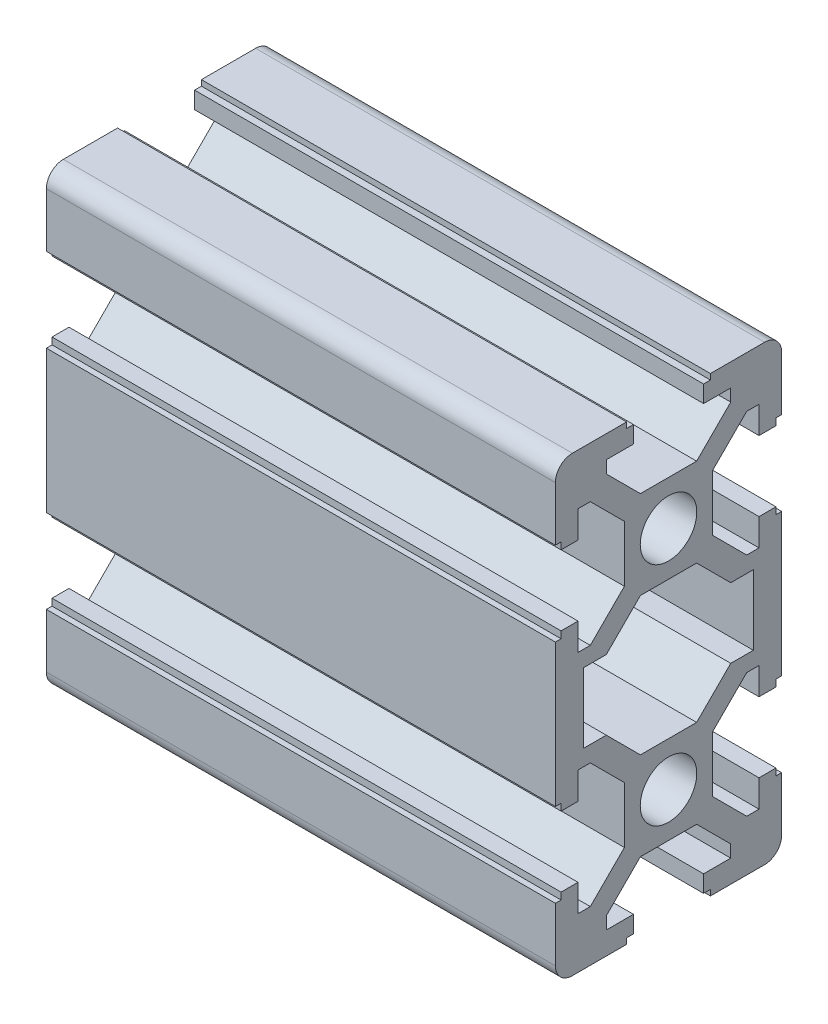
SolidWorks part; units mm, degrees
ref_plane "前视基准面" through (0, 0, 0) normal (0, 0, 1) x (1, 0, 0)
ref_plane "上视基准面" through (0, 0, 0) normal (0, 1, 0) x (1, 0, 0)
ref_plane "右视基准面" through (0, 0, 0) normal (1, 0, 0) x (0, 0, -1)
other "Configuration Table"
ref_plane "基准面1" through (0, 0, 9.923) normal (0, 0, 1) x (1, 0, 0)
sketch "草图1" plane through (0, 0, 9.923) normal (0, 0, 1) x (1, 0, 0)
  line L0 (-1048, 19.9963) -> (-1048, -20.0037)
  line L1 (-1048, -20.0037) -> (0, -20.0037)
  line L2 (0, -20.0037) -> (0, 19.9963)
  line L3 (0, 19.9963) -> (-1048, 19.9963)
extrude "凸台-拉伸1" add sketch "草图1" against normal blind 20
sketch "草图2" plane through (0, 0, 0) normal (1, 0, 0) x (0, 0, -1)
  line L0 (-3.023, 19.9963) -> (-3.023, 17.9963)
  line L1 (-3.023, 17.9963) -> (-5.423, 17.9963)
  line L2 (-5.423, 17.9963) -> (-5.423, 16.9105)
  line L3 (-5.423, 16.9105) -> (-2.4088, 13.8963)
  line L4 (-2.4088, 13.8963) -> (2.5628, 13.8963)
  line L5 (2.5628, 13.8963) -> (5.577, 16.9105)
  line L6 (5.577, 16.9105) -> (5.577, 17.9963)
  line L7 (5.577, 17.9963) -> (3.177, 17.9963)
  line L8 (3.177, 17.9963) -> (3.177, 19.9963)
  line L9 (3.177, 19.9963) -> (-3.023, 19.9963)
extrude "切除-拉伸1" cut sketch "草图2" against normal through all
sketch "草图3" plane through (0, 19.9963, 0) normal (0, 1, 0) x (-1, 0, 0)
  line L0 (9.0173, 3.023) -> (16.9827, 3.023)
  arc A0 (16.9827, 3.023) -> (9.0173, 3.023) centre (13, 0) ccw
extrude "切除-拉伸2" cut sketch "草图3" against normal up to next
sketch "草图4" plane through (-1048, 0, 0) normal (-1, 0, 0) x (0, 0, 1)
  line L0 (3.023, 19.4963) -> (3.628, 19.4963)
  line L1 (3.628, 19.4963) -> (3.628, 19.9963)
  line L2 (3.628, 19.9963) -> (3.023, 19.9963)
  line L3 (3.023, 19.9963) -> (3.023, 19.4963)
extrude "切除-拉伸3" cut sketch "草图4" against normal up to next
sketch "草图5" plane through (0, 0, 0) normal (1, 0, 0) x (0, 0, -1)
  line L0 (-3.023, -20.0037) -> (3.177, -20.0037)
  line L1 (3.177, -20.0037) -> (3.177, -18.0037)
  line L2 (3.177, -18.0037) -> (5.577, -18.0037)
  line L3 (5.577, -18.0037) -> (5.577, -16.9179)
  line L4 (5.577, -16.9179) -> (2.5628, -13.9037)
  line L5 (2.5628, -13.9037) -> (-2.4088, -13.9037)
  line L6 (-2.4088, -13.9037) -> (-5.423, -16.9179)
  line L7 (-5.423, -16.9179) -> (-5.423, -18.0037)
  line L8 (-5.423, -18.0037) -> (-3.023, -18.0037)
  line L9 (-3.023, -18.0037) -> (-3.023, -20.0037)
extrude "切除-拉伸4" cut sketch "草图5" against normal through all
sketch "草图6" plane through (0, -18.0037, 0) normal (0, 1, 0) x (-1, 0, 0)
  line L0 (9.0173, 3.023) -> (16.9827, 3.023)
  arc A0 (16.9827, 3.023) -> (9.0173, 3.023) centre (13, 0) ccw
extrude "切除-拉伸5" cut sketch "草图6" against normal through all
sketch "草图7" plane through (-1048, 0, 0) normal (-1, 0, 0) x (0, 0, 1)
  line L0 (3.023, -20.0037) -> (3.628, -20.0037)
  line L1 (3.628, -20.0037) -> (3.628, -19.5037)
  line L2 (3.628, -19.5037) -> (3.023, -19.5037)
  line L3 (3.023, -19.5037) -> (3.023, -20.0037)
extrude "切除-拉伸6" cut sketch "草图7" against normal up to next
sketch "草图8" plane through (0, -20.0037, 0) normal (0, -1, 0) x (1, 0, 0)
  line L0 (-9.1391, -3.177) -> (-16.8609, -3.177)
  arc A0 (-16.8609, -3.177) -> (-9.1391, -3.177) centre (-13, 0) ccw
extrude "切除-拉伸7" cut sketch "草图8" against normal up to next
sketch "草图9" plane through (-1048, 0, 0) normal (-1, 0, 0) x (0, 0, 1)
  line L0 (-3.177, -20.0037) -> (-3.177, -19.5037)
  line L1 (-3.177, -19.5037) -> (-3.782, -19.5037)
  line L2 (-3.782, -19.5037) -> (-3.782, -20.0037)
  line L3 (-3.782, -20.0037) -> (-3.177, -20.0037)
extrude "切除-拉伸8" cut sketch "草图9" against normal up to next
sketch "草图10" plane through (0, 0, 0) normal (1, 0, 0) x (0, 0, -1)
  line L0 (-3.628, 19.9963) -> (-3.628, 19.4963)
  line L1 (-3.628, 19.4963) -> (-3.023, 19.4963)
  line L2 (-3.023, 19.4963) -> (-3.023, 19.9963)
  line L3 (-3.023, 19.9963) -> (-3.628, 19.9963)
extrude "切除-拉伸9" cut sketch "草图10" against normal up to next
sketch "草图11" plane through (0, 17.9963, 0) normal (0, -1, 0) x (1, 0, 0)
  line L0 (-9.1391, -3.177) -> (-16.8609, -3.177)
  arc A0 (-16.8609, -3.177) -> (-9.1391, -3.177) centre (-13, 0) ccw
extrude "切除-拉伸10" cut sketch "草图11" against normal through all
sketch "草图12" plane through (0, 0, 0) normal (1, 0, 0) x (0, 0, -1)
  line L0 (3.177, 19.9963) -> (3.177, 19.4963)
  line L1 (3.177, 19.4963) -> (3.782, 19.4963)
  line L2 (3.782, 19.4963) -> (3.782, 19.9963)
  line L3 (3.782, 19.9963) -> (3.177, 19.9963)
extrude "切除-拉伸11" cut sketch "草图12" against normal up to next
sketch "草图13" plane through (0, 0, 0) normal (1, 0, 0) x (0, 0, -1)
  line L0 (10.077, 13.7013) -> (9.577, 13.7013)
  line L1 (9.577, 13.7013) -> (9.577, 13.0963)
  line L2 (9.577, 13.0963) -> (8.077, 13.0963)
  line L3 (8.077, 13.0963) -> (8.077, 15.4963)
  line L4 (8.077, 15.4963) -> (6.9912, 15.4963)
  line L5 (6.9912, 15.4963) -> (3.977, 12.4821)
  line L6 (3.977, 12.4821) -> (3.977, 7.5105)
  line L7 (3.977, 7.5105) -> (6.9912, 4.4963)
  line L8 (6.9912, 4.4963) -> (8.077, 4.4963)
  line L9 (8.077, 4.4963) -> (8.077, 6.8963)
  line L10 (8.077, 6.8963) -> (9.577, 6.8963)
  line L11 (9.577, 6.8963) -> (9.577, 6.2913)
  line L12 (9.577, 6.2913) -> (10.077, 6.2913)
  line L13 (10.077, 6.2913) -> (10.077, 13.7013)
extrude "切除-拉伸12" cut sketch "草图13" against normal through all
sketch "草图14" plane through (0, 0, 0) normal (1, 0, 0) x (0, 0, -1)
  line L0 (10.077, -6.2987) -> (9.577, -6.2987)
  line L1 (9.577, -6.2987) -> (9.577, -6.9037)
  line L2 (9.577, -6.9037) -> (8.077, -6.9037)
  line L3 (8.077, -6.9037) -> (8.077, -4.5037)
  line L4 (8.077, -4.5037) -> (6.9912, -4.5037)
  line L5 (6.9912, -4.5037) -> (3.977, -7.5179)
  line L6 (3.977, -7.5179) -> (3.977, -12.4895)
  line L7 (3.977, -12.4895) -> (6.9912, -15.5037)
  line L8 (6.9912, -15.5037) -> (8.077, -15.5037)
  line L9 (8.077, -15.5037) -> (8.077, -13.1037)
  line L10 (8.077, -13.1037) -> (9.577, -13.1037)
  line L11 (9.577, -13.1037) -> (9.577, -13.7087)
  line L12 (9.577, -13.7087) -> (10.077, -13.7087)
  line L13 (10.077, -13.7087) -> (10.077, -6.2987)
extrude "切除-拉伸13" cut sketch "草图14" against normal through all
sketch "草图15" plane through (0, 0, 0) normal (1, 0, 0) x (0, 0, -1)
  line L0 (3.782, -20.0037) -> (3.782, -19.5037)
  line L1 (3.782, -19.5037) -> (3.177, -19.5037)
  line L2 (3.177, -19.5037) -> (3.177, -20.0037)
  line L3 (3.177, -20.0037) -> (3.782, -20.0037)
extrude "切除-拉伸14" cut sketch "草图15" against normal up to next
sketch "草图16" plane through (0, 0, 0) normal (1, 0, 0) x (0, 0, -1)
  line L0 (-3.023, -20.0037) -> (-3.023, -19.5037)
  line L1 (-3.023, -19.5037) -> (-3.628, -19.5037)
  line L2 (-3.628, -19.5037) -> (-3.628, -20.0037)
  line L3 (-3.628, -20.0037) -> (-3.023, -20.0037)
extrude "切除-拉伸15" cut sketch "草图16" against normal up to next
sketch "草图17" plane through (0, 0, 0) normal (1, 0, 0) x (0, 0, -1)
  line L0 (-9.923, -13.7087) -> (-9.423, -13.7087)
  line L1 (-9.423, -13.7087) -> (-9.423, -13.1037)
  line L2 (-9.423, -13.1037) -> (-7.923, -13.1037)
  line L3 (-7.923, -13.1037) -> (-7.923, -15.5037)
  line L4 (-7.923, -15.5037) -> (-6.8372, -15.5037)
  line L5 (-6.8372, -15.5037) -> (-3.823, -12.4895)
  line L6 (-3.823, -12.4895) -> (-3.823, -7.5179)
  line L7 (-3.823, -7.5179) -> (-6.8372, -4.5037)
  line L8 (-6.8372, -4.5037) -> (-7.923, -4.5037)
  line L9 (-7.923, -4.5037) -> (-7.923, -6.9037)
  line L10 (-7.923, -6.9037) -> (-9.423, -6.9037)
  line L11 (-9.423, -6.9037) -> (-9.423, -6.2987)
  line L12 (-9.423, -6.2987) -> (-9.923, -6.2987)
  line L13 (-9.923, -6.2987) -> (-9.923, -13.7087)
extrude "切除-拉伸16" cut sketch "草图17" against normal through all
sketch "草图18" plane through (0, 0, 0) normal (1, 0, 0) x (0, 0, -1)
  line L0 (-9.923, 6.2913) -> (-9.423, 6.2913)
  line L1 (-9.423, 6.2913) -> (-9.423, 6.8963)
  line L2 (-9.423, 6.8963) -> (-7.923, 6.8963)
  line L3 (-7.923, 6.8963) -> (-7.923, 4.4963)
  line L4 (-7.923, 4.4963) -> (-6.8372, 4.4963)
  line L5 (-6.8372, 4.4963) -> (-3.823, 7.5105)
  line L6 (-3.823, 7.5105) -> (-3.823, 12.4821)
  line L7 (-3.823, 12.4821) -> (-6.8372, 15.4963)
  line L8 (-6.8372, 15.4963) -> (-7.923, 15.4963)
  line L9 (-7.923, 15.4963) -> (-7.923, 13.0963)
  line L10 (-7.923, 13.0963) -> (-9.423, 13.0963)
  line L11 (-9.423, 13.0963) -> (-9.423, 13.7013)
  line L12 (-9.423, 13.7013) -> (-9.923, 13.7013)
  line L13 (-9.923, 13.7013) -> (-9.923, 6.2913)
extrude "切除-拉伸17" cut sketch "草图18" against normal through all
sketch "草图19" plane through (-1048, 0, 0) normal (-1, 0, 0) x (0, 0, 1)
  line L0 (-3.782, 19.9963) -> (-3.782, 19.4963)
  line L1 (-3.782, 19.4963) -> (-3.177, 19.4963)
  line L2 (-3.177, 19.4963) -> (-3.177, 19.9963)
  line L3 (-3.177, 19.9963) -> (-3.782, 19.9963)
extrude "切除-拉伸18" cut sketch "草图19" against normal up to next
sketch "草图20" plane through (-1048, 0, 0) normal (-1, 0, 0) x (0, 0, 1)
  line L0 (2.4088, -3.0895) -> (7.423, -3.0895)
  line L1 (7.423, -3.0895) -> (7.423, 3.0821)
  line L2 (7.423, 3.0821) -> (2.4088, 3.0821)
  line L3 (2.4088, 3.0821) -> (2.4088, 6.0963)
  line L4 (2.4088, 6.0963) -> (-2.5628, 6.0963)
  line L5 (-2.5628, 6.0963) -> (-2.5628, 3.0821)
  line L6 (-2.5628, 3.0821) -> (-7.577, 3.0821)
  line L7 (-7.577, 3.0821) -> (-7.577, -3.0895)
  line L8 (-7.577, -3.0895) -> (-2.5628, -3.0895)
  line L9 (-2.5628, -3.0895) -> (-2.5628, -6.1037)
  line L10 (-2.5628, -6.1037) -> (2.4088, -6.1037)
  line L11 (2.4088, -6.1037) -> (2.4088, -3.0895)
extrude "切除-拉伸19" cut sketch "草图20" against normal through all
draft "拔模1" type of draft neutral plane draft angle 45 faces to draft 2 face at (-524, -4.5966, 2.4088) face at (-524, -4.5966, -2.5628) neutral plane through (0, -6.1037, -2.5628) neutral plane normal (0, 1, 0) parameters "D1"=45
draft "拔模2" type of draft neutral plane draft angle 45 faces to draft 2 face at (-524, 4.5892, -2.5628) face at (-524, 4.5892, 2.4088) neutral plane through (0, 6.0963, 2.4088) neutral plane normal (0, -1, 0) parameters "D1"=45
ref_plane "基准面2" through (0, 0, 0) normal (0, 0, -1) x (-1, 0, 0)
sketch "草图21" plane through (0, 0, 0) normal (0, 0, -1) x (-1, 0, 0)
  line L0 (8, 10.9963) -> (13, 10.9963)
  line L1 (13, 10.9963) -> (13, 16.4875)
  line L2 (13, 16.4875) -> (8, 16.4875)
  line L3 (8, 16.4875) -> (8, 10.9963)
  line L4 (13, 10.9963) -> (13, 16.4875) construction
revolve "切除-旋转1" cut sketch "草图21" angle 360 about L4
sketch "草图22" plane through (0, 0, 0) normal (0, 0, 1) x (1, 0, 0)
  line L0 (-8, -10.9963) -> (-13, -10.9963)
  line L1 (-13, -10.9963) -> (-13, -16.4949)
  line L2 (-13, -16.4949) -> (-8, -16.4949)
  line L3 (-8, -16.4949) -> (-8, -10.9963)
  line L4 (-13, -10.9963) -> (-13, -16.4949) construction
revolve "切除-旋转2" cut sketch "草图22" angle 360 about L4
hole_wizard "Ø5.0 (5) 直径孔1" positions "草图24" profile "草图23" hole size "Ø5.0" standard "ANSI Metric"
sketch "草图24" plane through (0, 0, 0) normal (1, 0, 0) x (0, 0, -1)
  point P0 (0.077, 9.9963)
sketch "草图23" plane through (0, 9.9963, -0.077) normal (0, 1, 0) x (0, 0, -1)
  line L0 (0, 0) -> (0, 1048)
  line L1 (0, 1048) -> (2.5, 1048)
  line L2 (2.5, 1048) -> (2.5, 0)
  line L5 (2.5, 0) -> (0, 0)
  line L11 (0, -6.35) -> (0, 107.95) construction
  dimension "通孔孔直径" = 5
  dimension "通孔孔深度" = 1048
hole_wizard "Ø5.0 (5) 直径孔2" positions "草图26" profile "草图25" hole size "Ø5.0" standard "ANSI Metric"
sketch "草图26" plane through (-1048, 0, 0) normal (-1, 0, 0) x (0, 0, 1)
  point P0 (-0.077, -10.0037)
sketch "草图25" plane through (-1048, -10.0037, -0.077) normal (0, 1, 0) x (0, 0, 1)
  line L0 (0, 0) -> (0, 1048)
  line L1 (0, 1048) -> (2.5, 1048)
  line L2 (2.5, 1048) -> (2.5, 0)
  line L5 (2.5, 0) -> (0, 0)
  line L11 (0, -6.35) -> (0, 107.95) construction
  dimension "通孔孔直径" = 5
  dimension "通孔孔深度" = 1048
fillet "圆角1" radius 1.5 4 edges at (-524, 19.9963, -10.077) (-524, -20.0037, -10.077) (-524, 19.9963, 9.923) (-524, -20.0037, 9.923)
sketch "草图27" plane through (0, 0, 0) normal (1, 0, 0) x (0, 0, -1)
  line L1 (-12.5, -22.5) -> (12.5, -22.5)
  line L2 (-12.5, -22.5) -> (-12.5, 22.5)
  line L3 (-12.5, 22.5) -> (12.5, 22.5)
  line L4 (12.5, -22.5) -> (12.5, 22.5)
  line L5 (-12.5, -22.5) -> (12.5, 22.5) construction
  line L6 (-12.5, 22.5) -> (12.5, -22.5) construction
  point P0 (0, 0)
  dimension "D1" = 45
  dimension "D2" = 25
extrude "切除-拉伸21" cut sketch "草图27" against normal blind 501.5
sketch "草图28" plane through (0, 0, 0) normal (1, 0, 0) x (0, 0, -1)
  line L4 (-12.5, -22.5) -> (12.5, -22.5)
  line L5 (12.5, -22.5) -> (12.5, 22.5)
  line L6 (12.5, 22.5) -> (-12.5, 22.5)
  line L7 (-12.5, 22.5) -> (-12.5, -22.5)
  line L8 (-12.5, -22.5) -> (12.5, -22.5)
  line L9 (12.5, -22.5) -> (12.5, 22.5)
  line L10 (12.5, 22.5) -> (-12.5, 22.5)
  line L11 (-12.5, 22.5) -> (-12.5, -22.5)
  dimension "D1" = 0
extrude "切除-拉伸22" cut sketch "草图28" along normal blind 501.5 from surface at -1048 starting at face at (-1048, -10.0037, 2.423)
